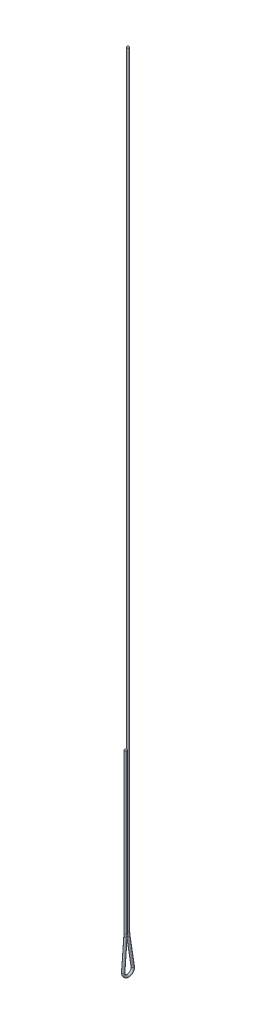
SolidWorks part; units mm, degrees
ref_plane "Front Plane" through (0, 0, 0) normal (0, 0, 1) x (1, 0, 0)
ref_plane "Top Plane" through (0, 0, 0) normal (0, 1, 0) x (1, 0, 0)
ref_plane "Right Plane" through (0, 0, 0) normal (1, 0, 0) x (0, 0, -1)
sketch "Sketch1" plane through (0, 0, 0) normal (1, 0, 0) x (0, 0, -1)
  line L1 (0, 21.5085) -> (0, 500)
  line L2 (0, 55) -> (0, -55) construction
  line L3 (55, 0) -> (-55, 0) construction
  line L4 (0.2263, 18.5085) -> (2.9661, 0.45)
  line L5 (-1.5, 20.7532) -> (-1.5, 120)
  line L6 (-1.5566, 19.2489) -> (-2.9915, 0.2256)
  circle A0 centre (0, 0) radius 2 construction
  arc A1 (-2.9915, 0.2256) -> (2.9661, 0.45) centre (0, 0) ccw
  arc A2 (0, 21.5085) -> (0.2263, 18.5085) centre (20, 21.5085) ccw
  arc A3 (-1.5, 20.7532) -> (-1.5566, 19.2489) centre (-21.5, 20.7532) cw
  point P15 (0, 20)
  point P18 (-1.5, 20)
  dimension "D1" = 4
  dimension "D2" = 6
  dimension "D8" = 20
  dimension "D3" = 20
  dimension "D4" = 480
  dimension "D5" = 1.5
  dimension "D6" = 100
  dimension "D7" = 20
ref_plane "Plane1" through (0, 120, 1.5) normal (0, 1, 0) x (-1, 0, 0)
sketch "Sketch2" plane through (0, 120, 1.5) normal (0, 1, 0) x (-1, 0, 0)
  circle A0 centre (0, 0) radius 0.75
  dimension "D1" = 1.5
sweep "Sweep1" add profiles "Sketch2" path "Sketch1"
